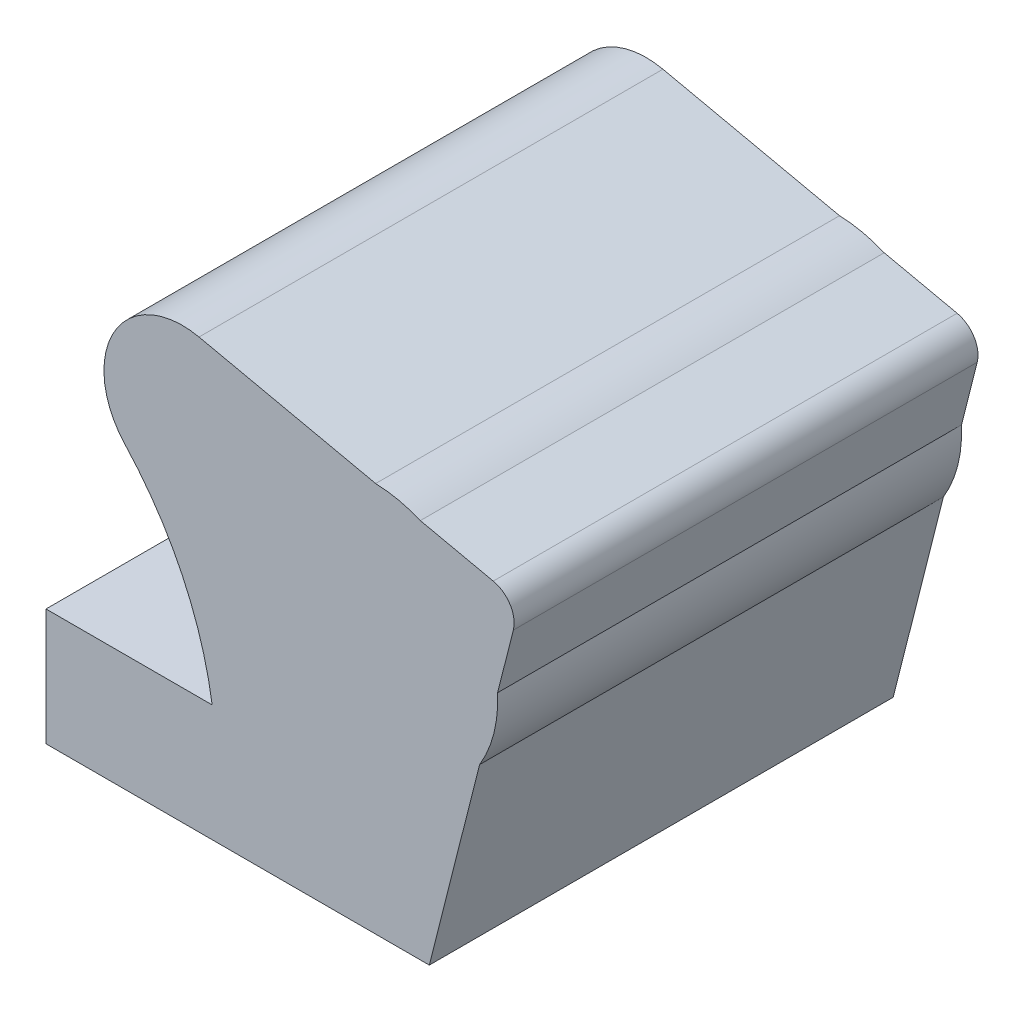
SolidWorks part; units mm, degrees
ref_plane "前视基准面" through (0, 0, 0) normal (0, 0, 1) x (1, 0, 0)
ref_plane "上视基准面" through (0, 0, 0) normal (0, 1, 0) x (1, 0, 0)
ref_plane "右视基准面" through (0, 0, 0) normal (1, 0, 0) x (0, 0, -1)
other "Configuration Table"
sketch "草图1" plane through (0, 0, 0) normal (0, 0, 1) x (1, 0, 0)
  line L0 (36.476, 29.1479) -> (56.672, 43.5041)
  line L1 (56.672, 74.4321) -> (92.4962, 74.4321)
  line L4 (0, 0) -> (144.001, 0)
  line L5 (144.001, 0) -> (134.5299, 27.1222)
  line L6 (117.0722, 27.1222) -> (123.3535, 49.2574)
  line L7 (134.5299, 27.1222) -> (117.0722, 27.1222)
  line L12 (0, 0) -> (0, 29.1479)
  line L16 (153.0865, 127.8443) -> (89.661, 141.6965)
  line L17 (86.0571, 125.1953) -> (126.841, 106.1775)
  line L20 (123.3535, 49.2574) -> (139.3032, 49.2574)
  line L22 (139.3032, 49.2574) -> (157.4114, 120.8535)
  line L23 (0, 29.1479) -> (36.476, 29.1479)
  line L26 (89.661, -23.7228) -> (89.661, 101.3733) construction
  line L27 (56.672, 43.5041) -> (56.672, 74.4321)
  arc A2 (92.4962, 74.4321) -> (73.6391, 113.7469) centre (18.9675, 63.3442) ccw
  arc A7 (157.4114, 120.8535) -> (153.0865, 127.8443) centre (151.866, 122.2561) ccw
  arc A8 (73.6391, 113.7469) -> (89.661, 141.6965) centre (86.0571, 125.1953) cw
  circle A15 centre (126.841, 106.1775) radius 27.2182
  point P0 (88.3175, 129.4356)
  dimension "D2" = 54.4365
  dimension "D3" = 74.36
  dimension "D4" = 5.72
  dimension "D1" = 106.1775
  dimension "D6" = 18.9675
  dimension "D7" = 36.476
  dimension "D8" = 56.672
  dimension "D9" = 25
  dimension "D10" = 89.661
  dimension "D11" = 151.866
  dimension "D12" = 92.4962
  dimension "D13" = 117.0722
  dimension "D14" = 123.3535
  dimension "D15" = 126.841
  dimension "D16" = 134.5299
  dimension "D17" = 139.3032
  dimension "D18" = 144.001
  dimension "D19" = 27.1222
  dimension "D20" = 29.1479
  dimension "D21" = 157.4114
  dimension "D22" = 43.5041
  dimension "D23" = 49.2574
  dimension "D24" = 45
extrude "凸台-拉伸1" add sketch "草图1" along normal mid plane 100 contours A2 A8 L16 A7 L22 L20 L6 L7 L5 L4 L12 L23 L0 L27 L1 | A15
sketch "草图2" plane through (0, 0, 50) normal (0, 0, 1) x (1, 0, 0)
  line L0 (123.3535, 49.2574) -> (56.672, 49.2574)
  line L1 (56.672, 43.5041) -> (56.672, 74.4321) construction
split "分割1" trim tools "草图2" bodies to split 106 resulting bodies 107 108
delete or keep bodies "实体-删除/保留 1" type keep bodies bodies 107
